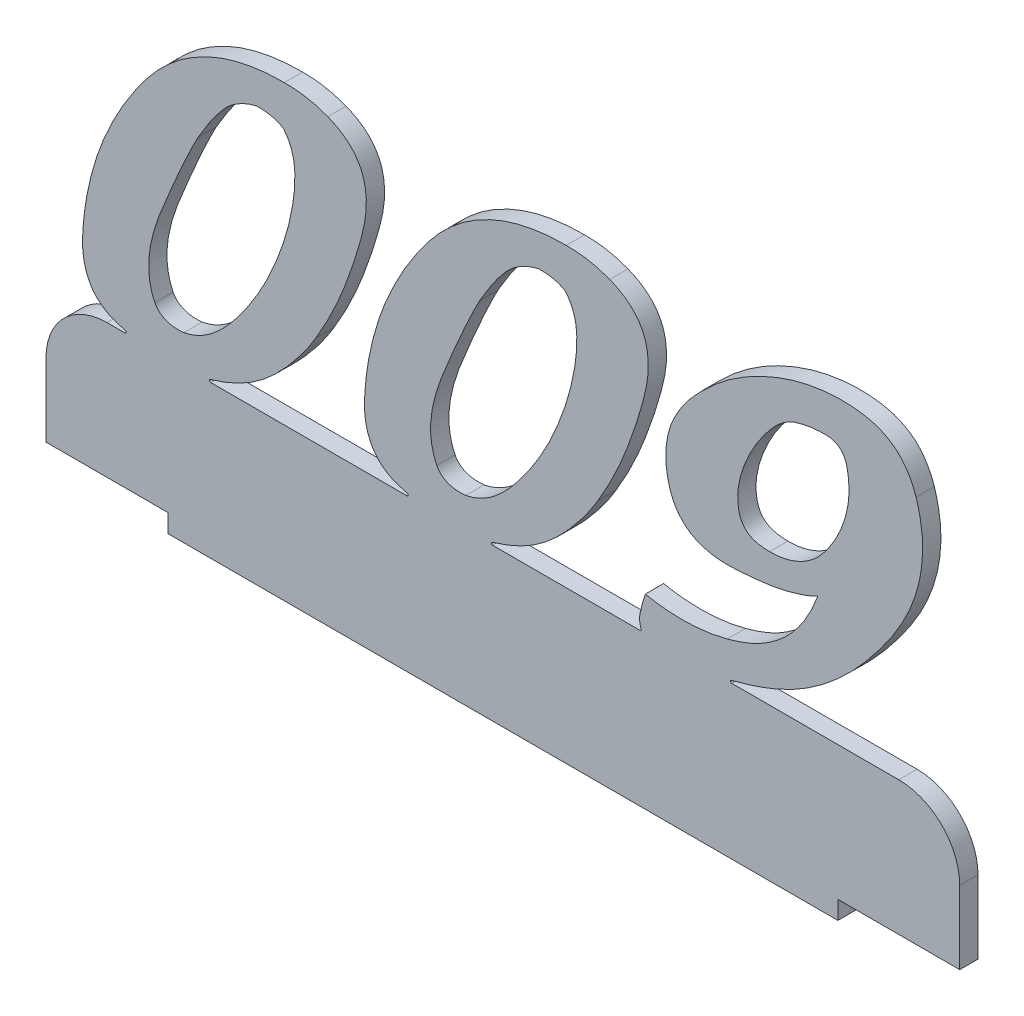
SolidWorks part; units mm, degrees
ref_plane "Front Plane" through (0, 0, 0) normal (0, 0, 1) x (1, 0, 0)
ref_plane "Top Plane" through (0, 0, 0) normal (0, 1, 0) x (1, 0, 0)
ref_plane "Right Plane" through (0, 0, 0) normal (1, 0, 0) x (0, 0, -1)
sketch "Sketch1" plane through (0, 0, 0) normal (0, 0, 1) x (1, 0, 0)
  line L0 (0, 20) -> (150, 20) construction
  line L1 (122.1085, 22) -> (150, 22)
  line L2 (0, 22) -> (0, 0)
  line L3 (0, 0) -> (20, 0)
  line L4 (150, 22) -> (150, 0)
  line L5 (0, 22) -> (14.8507, 22)
  line L6 (25.5185, 22) -> (61.1369, 22)
  line L7 (71.8047, 22) -> (97.8495, 22)
  line L8 (110.8451, 22) -> (122.1085, 22)
  line L11 (130, 0) -> (150, 0)
  line L13 (20, 0) -> (20, -3)
  line L14 (20, -3) -> (130, -3)
  line L15 (130, 0) -> (130, -3)
  spline S0 degree 3 poles (38.9856, 64.0716) (38.3843, 64.4811) (36.919, 64.9872) (35.3812, 65.1145) (34.5681, 65.0684) knots 0 0 0 0 0.469699 1 1 1 1
  spline S1 degree 3 poles (34.5681, 65.0684) (33.4234, 64.8277) (31.8053, 64.1502) (29.917, 62.7726) (27.609, 60.1946) (26.0753, 57.743) (24.9316, 55.7643) knots 0 0 0 0 0.25259 0.375811 0.50377 1 1 1 1
  spline S2 degree 3 poles (24.9316, 55.7643) (24.4754, 54.9662) (23.8771, 53.6497) (22.9856, 51.8306) (22.2722, 50.2491) (21.5078, 48.5298) (20.7073, 46.6631) (19.8507, 44.6669) (18.9786, 42.5786) (18.1856, 40.4804) (17.554, 38.453) (17.1132, 36.5459) (16.8703, 34.7529) (16.823, 33.0736) (17.0247, 31.0479) (17.4442, 29.6243) (17.8754, 28.7705) knots 0 0 0 0 0.095871 0.150957 0.21155 0.277044 0.347448 0.42366 0.503899 0.583776 0.657815 0.725493 0.787949 0.846481 0.90051 1 1 1 1
  spline S3 degree 3 poles (17.8754, 28.7705) (18.2338, 28.0275) (19.7333, 26.8202) (21.6462, 26.8037) (22.6252, 26.8745) knots 0 0 0 0 0.446154 1 1 1 1
  spline S4 degree 3 poles (22.6252, 26.8745) (24.0827, 27.1489) (26.2393, 28.1673) (28.7716, 30.3351) (30.722, 32.4923) (32.5888, 34.9778) (34.3504, 37.6518) (35.9408, 40.4783) (37.3353, 43.4345) (38.5335, 46.4515) (39.525, 49.4636) (40.2437, 52.4521) (40.7482, 55.3427) (40.9179, 58.0444) (40.716, 61.075) (39.8411, 63.0635) (38.9856, 64.0716) knots 0 0 0 0 0.099523 0.157976 0.224341 0.295662 0.367825 0.440561 0.514606 0.588508 0.65979 0.72866 0.796042 0.857776 0.911265 1 1 1 1
  spline S5 degree 3 poles (14.8507, 22) (13.8332, 22.1857) (12.2947, 22.5475) (10.3146, 23.2449) (9.0082, 24.0948) (7.8983, 25.1138) (7.0684, 26.3911) (6.4629, 27.8626) (5.9093, 30.2275) (5.9789, 32.1472) (6.0693, 33.4617) knots 0.385714 0.385714 0.385714 0.385714 0.501388 0.5623 0.61932 0.674488 0.729675 0.788153 0.851799 1 1 1 1
  spline S6 degree 3 poles (6.0693, 33.4617) (6.2362, 35.6898) (6.7254, 39.0154) (7.8548, 43.3522) (8.9176, 46.5615) (10.2722, 49.6949) (11.8102, 52.8007) (13.6179, 55.8439) (15.625, 58.811) (17.8226, 61.6003) (20.2968, 64.0192) (22.9391, 66.1068) (25.8193, 67.7542) (28.8548, 69.102) (33.2772, 70.3243) (36.7559, 70.7091) (39.1224, 70.6783) knots 0 0 0 0 0.122246 0.183381 0.245051 0.307032 0.370011 0.434579 0.500535 0.565958 0.62848 0.689454 0.749684 0.809559 0.870725 1 1 1 1
  spline S7 degree 3 poles (39.1224, 70.6783) (40.3827, 70.6678) (42.8255, 70.5243) (45.1657, 69.8145) (46.2569, 69.4078) knots 0 0 0 0 0.519885 1 1 1 1
  spline S8 degree 3 poles (46.2569, 69.4078) (47.5244, 68.8925) (49.3195, 67.8991) (51.0588, 65.9162) (51.9683, 64.2427) (52.4836, 62.3378) (52.6489, 60.2208) (52.4558, 57.89) (51.7064, 54.5506) (50.4279, 50.3842) (48.1267, 44.0806) (45.9298, 39.6543) (44.2632, 36.9019) knots 0 0 0 0 0.111906 0.162582 0.212593 0.265416 0.321766 0.384451 0.454781 0.599581 0.738515 1 1 1 1
  spline S9 degree 3 poles (44.2632, 36.9019) (43.1717, 35.0447) (41.3014, 32.4742) (38.552, 29.3512) (36.3833, 27.282) (34.0009, 25.4743) (31.3212, 23.9785) (28.4706, 22.8197) (26.487, 22.2405) (25.5185, 22) knots 0 0 0 0 0.25786 0.380114 0.498337 0.616577 0.737567 0.865048 0.984702 0.984702 0.984702 0.984702
  spline S10 degree 3 poles (85.2718, 64.0716) (84.6705, 64.4811) (83.2052, 64.9872) (81.6674, 65.1145) (80.8542, 65.0684) knots 0 0 0 0 0.469699 1 1 1 1
  spline S11 degree 3 poles (80.8542, 65.0684) (79.7095, 64.8277) (78.0915, 64.1502) (76.2031, 62.7726) (73.8952, 60.1946) (72.3615, 57.743) (71.2178, 55.7643) knots 0 0 0 0 0.25259 0.375811 0.50377 1 1 1 1
  spline S12 degree 3 poles (71.2178, 55.7643) (70.7615, 54.9662) (70.1633, 53.6497) (69.2718, 51.8306) (68.5583, 50.2491) (67.7939, 48.5298) (66.9935, 46.6631) (66.1369, 44.6669) (65.2648, 42.5786) (64.4718, 40.4804) (63.8402, 38.453) (63.3993, 36.5459) (63.1564, 34.7529) (63.1091, 33.0736) (63.3108, 31.0479) (63.7303, 29.6243) (64.1615, 28.7705) knots 0 0 0 0 0.095871 0.150957 0.21155 0.277044 0.347448 0.42366 0.503899 0.583776 0.657815 0.725493 0.787949 0.846481 0.90051 1 1 1 1
  spline S13 degree 3 poles (64.1615, 28.7705) (64.52, 28.0275) (66.0194, 26.8202) (67.9323, 26.8037) (68.9113, 26.8745) knots 0 0 0 0 0.446154 1 1 1 1
  spline S14 degree 3 poles (68.9113, 26.8745) (70.3688, 27.1489) (72.5254, 28.1673) (75.0577, 30.3351) (77.0082, 32.4923) (78.875, 34.9778) (80.6365, 37.6518) (82.227, 40.4783) (83.6215, 43.4345) (84.8197, 46.4515) (85.8112, 49.4636) (86.5299, 52.4521) (87.0344, 55.3427) (87.204, 58.0444) (87.0022, 61.075) (86.1273, 63.0635) (85.2718, 64.0716) knots 0 0 0 0 0.099523 0.157976 0.224341 0.295662 0.367825 0.440561 0.514606 0.588508 0.65979 0.72866 0.796042 0.857776 0.911265 1 1 1 1
  spline S15 degree 3 poles (61.1369, 22) (60.1194, 22.1857) (58.5808, 22.5475) (56.6008, 23.2449) (55.2944, 24.0948) (54.1844, 25.1138) (53.3545, 26.3911) (52.7491, 27.8626) (52.1954, 30.2275) (52.2651, 32.1472) (52.3554, 33.4617) knots 0.385714 0.385714 0.385714 0.385714 0.501388 0.5623 0.61932 0.674488 0.729675 0.788153 0.851799 1 1 1 1
  spline S16 degree 3 poles (52.3554, 33.4617) (52.5223, 35.6898) (53.0115, 39.0154) (54.1409, 43.3522) (55.2037, 46.5615) (56.5584, 49.6949) (58.0964, 52.8007) (59.9041, 55.8439) (61.9112, 58.811) (64.1087, 61.6003) (66.583, 64.0192) (69.2252, 66.1068) (72.1055, 67.7542) (75.141, 69.102) (79.5634, 70.3243) (83.0421, 70.7091) (85.4086, 70.6783) knots 0 0 0 0 0.122246 0.183381 0.245051 0.307032 0.370011 0.434579 0.500535 0.565958 0.62848 0.689454 0.749684 0.809559 0.870725 1 1 1 1
  spline S17 degree 3 poles (85.4086, 70.6783) (86.6688, 70.6678) (89.1117, 70.5243) (91.4518, 69.8145) (92.5431, 69.4078) knots 0 0 0 0 0.519885 1 1 1 1
  spline S18 degree 3 poles (92.5431, 69.4078) (93.8106, 68.8925) (95.6057, 67.8991) (97.345, 65.9162) (98.2545, 64.2427) (98.7698, 62.3378) (98.9351, 60.2208) (98.742, 57.89) (97.9926, 54.5506) (96.7141, 50.3842) (94.4129, 44.0806) (92.216, 39.6543) (90.5493, 36.9019) knots 0 0 0 0 0.111906 0.162582 0.212593 0.265416 0.321766 0.384451 0.454781 0.599581 0.738515 1 1 1 1
  spline S19 degree 3 poles (90.5493, 36.9019) (89.4578, 35.0447) (87.5875, 32.4742) (84.8382, 29.3512) (82.6695, 27.282) (80.2871, 25.4743) (77.6073, 23.9785) (74.7567, 22.8197) (72.7732, 22.2405) (71.8047, 22) knots 0 0 0 0 0.25786 0.380114 0.498337 0.616577 0.737567 0.865048 0.984702 0.984702 0.984702 0.984702
  spline S20 degree 3 poles (131.4993, 62.156) (131.3472, 62.9874) (130.7353, 64.2196) (129.1466, 64.9935) (126.5215, 65.148) (124.3289, 64.7587) (122.6642, 64.2084) knots 0 0 0 0 0.248411 0.362075 0.494721 1 1 1 1
  spline S21 degree 3 poles (122.6642, 64.2084) (121.8034, 63.8444) (120.5396, 63.0029) (119.0548, 61.4504) (117.8779, 59.9805) (116.7664, 58.3433) (115.7661, 56.6382) (114.9486, 54.878) (114.2529, 53.125) (113.7907, 51.3869) (113.5321, 49.7202) (113.5549, 48.1426) (113.7942, 46.6789) (114.3902, 45.3707) (115.9791, 43.9917) (117.683, 43.849) (118.7745, 43.8214) knots 0 0 0 0 0.103918 0.167103 0.238919 0.313673 0.387561 0.459053 0.529882 0.597547 0.659189 0.71731 0.772735 0.823742 0.874177 1 1 1 1
  spline S22 degree 3 poles (118.7745, 43.8214) (119.7055, 43.8236) (121.0893, 43.9579) (122.8254, 44.5042) (124.0574, 45.0261) (125.2021, 45.741) (126.6927, 46.887) (127.6061, 48.0017) (128.1959, 48.7666) knots 0 0 0 0 0.252638 0.372665 0.492016 0.613999 0.737214 1 1 1 1
  spline S23 degree 3 poles (128.1959, 48.7666) (128.9343, 49.8287) (129.9324, 51.4506) (130.8774, 53.7483) (131.3803, 55.4252) (131.7358, 57.1043) (131.8719, 59.36) (131.7413, 61.0515) (131.4993, 62.156) knots 0 0 0 0 0.273616 0.400153 0.523827 0.643149 0.761819 1 1 1 1
  spline S24 degree 3 poles (142.8363, 63.6024) (143.4021, 61.792) (143.9791, 58.9804) (143.9068, 55.1774) (143.5147, 52.3146) (142.7395, 49.4292) (141.5971, 46.526) (140.0666, 43.6153) (138.2132, 40.741) (136.144, 37.9853) (134.0191, 35.3826) (131.8059, 33.0373) (129.5375, 30.9172) (127.2071, 29.0331) (124.0585, 26.8595) (121.5488, 25.5382) (119.83, 24.8221) knots 0 0 0 0 0.116715 0.174354 0.232938 0.293809 0.35743 0.424203 0.495481 0.567285 0.6358 0.701771 0.765206 0.826401 0.885685 1 1 1 1
  spline S25 degree 3 poles (119.83, 24.8221) (116.9286, 23.6122) (113.9188, 22.6607) (110.8451, 22) knots 0 0 0 0 0.501799 0.501799 0.501799 0.501799
  spline S27 degree 2 poles (97.8495, 22) (97.7417, 22.1704) (97.6642, 22.3788) knots 0.784122 0.784122 0.784122 1 1 1
  spline S28 degree 2 poles (97.6642, 22.3788) (97.2672, 23.5165) (97.5861, 24.6853) knots 0 0 0 1 1 1
  spline S29 degree 2 poles (97.5861, 24.6853) (97.8942, 26.1668) (98.3875, 27.5977) knots 0 0 0 1 1 1
  spline S30 degree 3 poles (98.3875, 27.5977) (100.6408, 27.123) (105.1765, 26.7438) (109.6873, 27.3486) (111.8355, 27.93) knots 0 0 0 0 0.508624 1 1 1 1
  spline S31 degree 3 poles (111.8355, 27.93) (113.5651, 28.3953) (116.0902, 29.2581) (119.0721, 31.072) (121.064, 32.6331) (122.8132, 34.4841) (124.928, 37.2967) (126.0501, 39.7502) (126.6908, 41.4367) knots 0 0 0 0 0.256976 0.377834 0.497939 0.617932 0.741164 1 1 1 1
  spline S32 degree 3 poles (126.6908, 41.4367) (125.8126, 40.9813) (124.3855, 40.4124) (122.3626, 39.8128) (120.6753, 39.3965) (118.8599, 39.0702) (116.9151, 38.8197) (114.848, 38.6322) (112.7115, 38.4765) (110.6196, 38.49) (108.6868, 38.7762) (106.9885, 39.3228) (105.4951, 40.105) (104.2682, 41.1884) (102.8813, 43.0123) (102.3289, 44.7076) (102.0818, 45.8737) knots 0 0 0 0 0.103259 0.160127 0.220402 0.284772 0.352757 0.425249 0.501656 0.576564 0.643393 0.704973 0.762247 0.818228 0.874604 1 1 1 1
  spline S33 degree 3 poles (102.0818, 45.8737) (101.8358, 47.0277) (101.6579, 48.7896) (101.8713, 51.1221) (102.2417, 52.8237) (102.8366, 54.494) (103.6757, 56.1128) (104.6882, 57.7268) (106.347, 59.7937) (108.6903, 62.1988) (111.7778, 64.7698) (115.135, 66.9631) (118.7079, 68.7392) (122.3917, 70.1173) (126.1048, 70.9798) (129.7831, 71.3732) (132.8001, 71.2505) (135.1053, 70.8769) (136.6905, 70.415) (138.1123, 69.7352) (139.4013, 68.9014) (140.5124, 67.8419) (141.7912, 66.1356) (142.5088, 64.6631) (142.8363, 63.6024) knots 0 0 0 0 0.060653 0.090244 0.120065 0.149935 0.181086 0.213602 0.247702 0.317092 0.385824 0.453814 0.522704 0.590512 0.655496 0.718108 0.780118 0.810012 0.837982 0.864646 0.890745 0.916565 0.943089 1 1 1 1
  dimension "D1" = 150
  dimension "D2" = 3
  dimension "D3" = 20
  dimension "D4" = 20
  dimension "D5" = 20
extrude "Boss-Extrude1" add sketch "Sketch1" along normal blind 3
fillet "Fillet1" radius 10 2 edges at (0, 22, 1.5) (150, 22, 1.5)
fillet "Fillet2" radius 0.2 6 edges at (25.5185, 22, 1.5) (71.8047, 22, 1.5) (110.8451, 22, 1.5) (97.8495, 22, 1.5) (61.1369, 22, 1.5) (14.8507, 22, 1.5)
